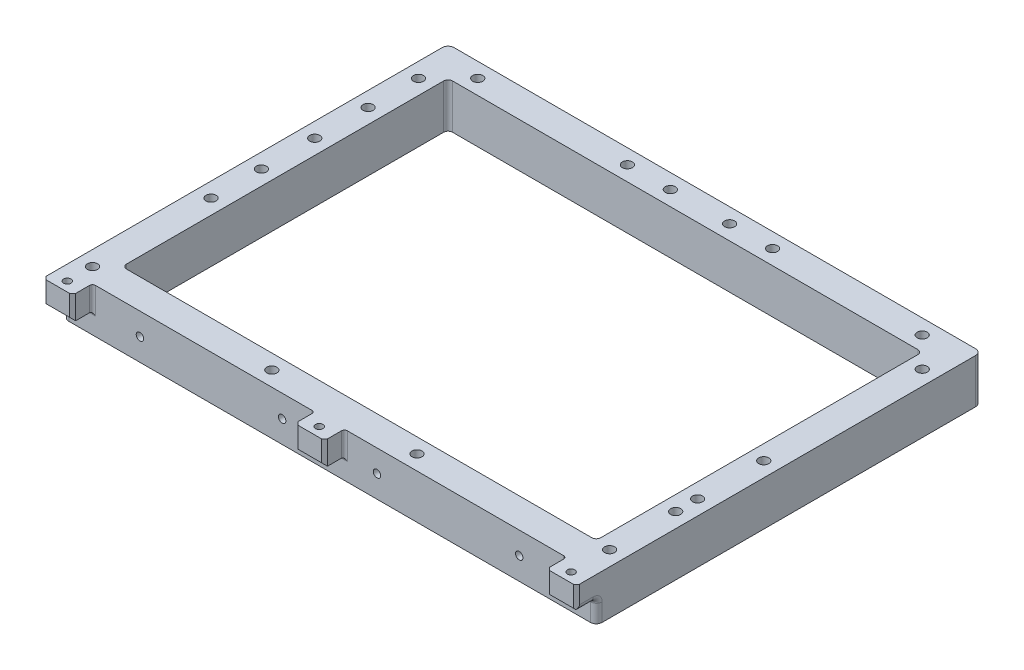
SolidWorks part; units mm, degrees
material "PLA"
ref_plane "Front Plane" through (0, 0, 0) normal (0, 0, 1) x (1, 0, 0)
ref_plane "Top Plane" through (0, 0, 0) normal (0, 1, 0) x (1, 0, 0)
ref_plane "Right Plane" through (0, 0, 0) normal (1, 0, 0) x (0, 0, -1)
sketch "Sketch1" plane through (0, 0, 0) normal (0, 1, 0) x (1, 0, 0)
  line L1 (-114.3, 82.55) -> (114.3, 82.55)
  line L2 (-114.3, 82.55) -> (-114.3, -82.55)
  line L3 (-114.3, -82.55) -> (114.3, -82.55)
  line L4 (114.3, 82.55) -> (114.3, -82.55)
  line L5 (-114.3, 82.55) -> (114.3, -82.55) construction
  line L6 (-114.3, -82.55) -> (114.3, 82.55) construction
  line L7 (-101.6, 69.85) -> (101.6, 69.85)
  line L8 (-101.6, 69.85) -> (-101.6, -69.85)
  line L9 (-101.6, -69.85) -> (101.6, -69.85)
  line L10 (101.6, 69.85) -> (101.6, -69.85)
  line L11 (-101.6, 69.85) -> (101.6, -69.85) construction
  line L12 (-101.6, -69.85) -> (101.6, 69.85) construction
  point P0 (0, 0)
  point P6 (0, 0)
  dimension "D1" = 165.1
  dimension "D2" = 139.7
  dimension "D3" = 228.6
  dimension "D4" = 203.2
extrude "Frame" add sketch "Sketch1" along normal blind 19.05
sketch "Sketch2" plane through (0, 19.05, 0) normal (0, 1, 0) x (1, 0, 0)
  line L0 (-114.3, 82.55) -> (-114.3, -82.55) construction
  line L1 (114.3, 82.55) -> (-114.3, 82.55) construction
  line L2 (0, 0) -> (0, 50000) construction
  line L3 (-101.6, 63.5) -> (-114.3, 63.5) construction
  line L4 (-101.6, 69.85) -> (-101.6, -69.85) construction
  line L5 (-95.25, 69.85) -> (-95.25, 82.55) construction
  line L6 (101.6, 69.85) -> (-101.6, 69.85) construction
  circle A0 centre (-95.25, 76.2) radius 2.159
  circle A1 centre (-107.95, 63.5) radius 2.159
  circle A2 centre (95.25, 76.2) radius 2.159
  circle A3 centre (107.95, 63.5) radius 2.159
  dimension "D1" = 4.318
  dimension "D2" = 4.318
  dimension "D3" = 19.05
  dimension "D6" = 19.05
extrude "FrontWall_mountingHoles" cut sketch "Sketch2" against normal blind 7.112
sketch "Sketch3" plane through (0, 0, 82.55) normal (0, 0, 1) x (1, 0, 0)
  line L0 (0, 0) -> (0, 50000) construction
  line L1 (-114.3, 0) -> (114.3, 0) construction
  line L2 (114.3, 19.05) -> (101.6, 19.05)
  line L3 (-114.3, 19.05) -> (114.3, 19.05) construction
  line L4 (101.6, 19.05) -> (101.6, 8.89)
  line L5 (101.6, 8.89) -> (114.3, 8.89)
  line L6 (114.3, 19.05) -> (114.3, 0) construction
  line L7 (114.3, 8.89) -> (114.3, 19.05)
  line L8 (-6.35, 19.05) -> (6.35, 19.05)
  line L9 (6.35, 19.05) -> (6.35, 8.89)
  line L10 (6.35, 8.89) -> (-6.35, 8.89)
  line L11 (-6.35, 19.05) -> (-6.35, 8.89)
  line L12 (-114.3, 8.89) -> (-114.3, 19.05)
  line L13 (-101.6, 8.89) -> (-114.3, 8.89)
  line L14 (-101.6, 19.05) -> (-101.6, 8.89)
  line L15 (-114.3, 19.05) -> (-101.6, 19.05)
  point P4 (0, 0)
  point P19 (0, 8.89)
  point P20 (0, 19.05)
  dimension "D1" = 10.16
  dimension "D2" = 12.7
  dimension "D3" = 10.16
  dimension "D4" = 12.7
extrude "Boss-Extrude2" add sketch "Sketch3" along normal blind 8.89
sketch "Sketch4" plane through (0, 19.05, 0) normal (0, 1, 0) x (1, 0, 0)
  line L0 (-114.3, -82.55) -> (114.3, -82.55) construction
  line L1 (-107.95, -91.44) -> (-107.95, -82.55) construction
  line L2 (-107.95, -82.55) -> (-107.95, -86.995) construction
  line L3 (-107.95, -86.995) -> (-101.6, -86.995) construction
  line L4 (0, -82.55) -> (0, -91.44) construction
  line L12 (114.3, -91.44) -> (114.3, 82.55)
  line L13 (114.3, 82.55) -> (-114.3, 82.55)
  line L14 (-114.3, 82.55) -> (-114.3, -91.44)
  line L15 (-114.3, -91.44) -> (-101.6, -91.44)
  line L16 (-101.6, -91.44) -> (-101.6, -82.55)
  line L17 (-101.6, -82.55) -> (-6.35, -82.55)
  line L18 (-6.35, -82.55) -> (-6.35, -91.44)
  line L19 (-6.35, -91.44) -> (6.35, -91.44)
  line L20 (6.35, -91.44) -> (6.35, -82.55)
  line L21 (6.35, -82.55) -> (101.6, -82.55)
  line L22 (101.6, -82.55) -> (101.6, -91.44)
  line L23 (101.6, -91.44) -> (114.3, -91.44)
  line L24 (114.3, -91.44) -> (114.3, 82.55) construction
  line L25 (114.3, 82.55) -> (-114.3, 82.55) construction
  line L26 (-114.3, 82.55) -> (-114.3, -91.44) construction
  line L27 (-114.3, -91.44) -> (-101.6, -91.44) construction
  line L28 (-101.6, -91.44) -> (-101.6, -82.55) construction
  line L29 (-101.6, -82.55) -> (-6.35, -82.55) construction
  line L30 (-6.35, -82.55) -> (-6.35, -91.44) construction
  line L31 (-6.35, -91.44) -> (6.35, -91.44) construction
  line L32 (6.35, -91.44) -> (6.35, -82.55) construction
  line L33 (6.35, -82.55) -> (101.6, -82.55) construction
  line L34 (101.6, -82.55) -> (101.6, -91.44) construction
  line L35 (101.6, -91.44) -> (114.3, -91.44) construction
  circle A0 centre (-107.95, -86.995) radius 1.5875
  circle A1 centre (0, -86.995) radius 1.5875
  circle A2 centre (107.95, -86.995) radius 1.5875
  dimension "D2" = 3.175
  dimension "D3" = 3.175
  dimension "D1" = 0
extrude "Cut-Extrude2" cut sketch "Sketch4" against normal through all
sketch "Sketch5" plane through (0, 0, 82.55) normal (0, 0, 1) x (1, 0, 0)
  line L0 (0, 0) -> (0, 19.05) construction
  line L1 (-114.3, 0) -> (114.3, 0) construction
  line L2 (6.35, 19.05) -> (-6.35, 19.05) construction
  circle A0 centre (-20.32, 9.525) radius 1.5875
  circle A1 centre (-81.28, 9.525) radius 1.5875
  circle A2 centre (81.28, 9.525) radius 1.5875
  circle A3 centre (20.32, 9.525) radius 1.5875
  dimension "D1" = 3.175
  dimension "D2" = 3.175
  dimension "D3" = 20.32
  dimension "D4" = 81.28
  dimension "D5" = 9.525
  dimension "D6" = 9.525
extrude "Cut-Extrude3" cut sketch "Sketch5" against normal up to surface (12.7 mm away) up to face at (0, 9.525, 69.85)
fillet "Fillet3" radius 1.905 4 edges at (101.6, 9.525, 69.85) (-101.6, 9.525, 69.85) (-101.6, 9.525, -69.85) (101.6, 9.525, -69.85)
sketch "Sketch6" plane through (0, 19.05, 0) normal (0, 1, 0) x (1, 0, 0)
  line L0 (114.3, -91.44) -> (114.3, 82.55) construction
  line L2 (99.695, 69.85) -> (-99.695, 69.85) construction
  circle A0 centre (107.95, -4.445) radius 2.159
  circle A1 centre (107.95, -32.766) radius 2.159
  circle A2 centre (107.95, -42.164) radius 2.159
  circle A3 centre (107.95, -70.485) radius 2.159
  dimension "D1" = 4.318
  dimension "D2" = 4.318
  dimension "D3" = 4.318
  dimension "D4" = 4.318
  dimension "D5" = 6.35
  dimension "D6" = 6.35
  dimension "D7" = 6.35
  dimension "D8" = 6.35
  dimension "D11" = 112.014
  dimension "D12" = 140.335
  dimension "D9" = 74.295
  dimension "D10" = 102.616
extrude "Linkage_RHS_MountingHoles" cut sketch "Sketch6" against normal blind 7.112
sketch "Sketch7" plane through (0, 19.05, 0) normal (0, 1, 0) x (1, 0, 0)
  line L0 (-114.3, 82.55) -> (-114.3, -91.44) construction
  line L1 (99.695, 69.85) -> (-99.695, 69.85) construction
  circle A0 centre (-107.95, 41.91) radius 2.159
  circle A1 centre (-107.95, 19.05) radius 2.159
  circle A2 centre (-107.95, -3.81) radius 2.159
  dimension "D1" = 4.318
  dimension "D2" = 4.318
  dimension "D3" = 4.318
  dimension "D5" = 6.35
  dimension "D4" = 6.35
  dimension "D6" = 27.94
  dimension "D7" = 50.8
  dimension "D8" = 73.66
  dimension "D9" = 6.35
extrude "Linkage-LHS-MountingHoles" cut sketch "Sketch7" against normal blind 7.112
sketch "Sketch11" plane through (0, 0, 91.44) normal (0, 0, 1) x (1, 0, 0)
  line L4 (-114.3, 8.89) -> (-101.6, 8.89)
  line L5 (-101.6, 8.89) -> (-101.6, 19.05)
  line L6 (-101.6, 19.05) -> (-114.3, 19.05)
  line L7 (-114.3, 19.05) -> (-114.3, 8.89)
  line L8 (-114.3, 8.89) -> (-101.6, 8.89)
  line L9 (-101.6, 8.89) -> (-101.6, 19.05)
  line L10 (-101.6, 19.05) -> (-114.3, 19.05)
  line L11 (-114.3, 19.05) -> (-114.3, 8.89)
  line L12 (6.35, 8.89) -> (6.35, 19.05)
  line L13 (6.35, 19.05) -> (-6.35, 19.05)
  line L14 (-6.35, 19.05) -> (-6.35, 8.89)
  line L15 (-6.35, 8.89) -> (6.35, 8.89)
  line L16 (6.35, 8.89) -> (6.35, 19.05)
  line L17 (6.35, 19.05) -> (-6.35, 19.05)
  line L18 (-6.35, 19.05) -> (-6.35, 8.89)
  line L19 (-6.35, 8.89) -> (6.35, 8.89)
  line L20 (114.3, 8.89) -> (114.3, 19.05)
  line L21 (114.3, 19.05) -> (101.6, 19.05)
  line L22 (101.6, 19.05) -> (101.6, 8.89)
  line L23 (101.6, 8.89) -> (114.3, 8.89)
  line L24 (114.3, 8.89) -> (114.3, 19.05)
  line L25 (114.3, 19.05) -> (101.6, 19.05)
  line L26 (101.6, 19.05) -> (101.6, 8.89)
  line L27 (101.6, 8.89) -> (114.3, 8.89)
  dimension "D1" = 0
  dimension "D2" = 0
  dimension "D3" = 0
extrude "Cut-Extrude6" cut sketch "Sketch11" against normal blind 0.381
fillet "Fillet2" radius 1.27 7 edges at (107.95, 8.89, 82.55) (0, 8.89, 82.55) (-107.95, 8.89, 82.55) (101.6, 13.97, 82.55) (6.35, 13.97, 82.55) (-6.35, 13.97, 82.55) (-101.6, 13.97, 82.55)
chamfer "Chamfer1" distance 1.27 angle 45 9 edges at (101.6, 13.97, 91.059) (6.35, 13.97, 91.059) (-6.35, 13.97, 91.059) (-101.6, 13.97, 91.059) (107.95, 8.89, 91.059) (0, 8.89, 91.059) (-107.95, 8.89, 91.059) (114.3, 13.97, 91.059) (-114.3, 13.97, 91.059)
sketch "Sketch12" plane through (0, 19.05, 0) normal (0, 1, 0) x (1, 0, 0)
  line L0 (0, 82.55) -> (0, 0) construction
  line L1 (114.3, 82.55) -> (-114.3, 82.55) construction
  line L2 (0, 0) -> (-101.6, 0) construction
  line L3 (-101.6, 67.945) -> (-101.6, -67.945) construction
  line L4 (99.695, 69.85) -> (-99.695, 69.85) construction
  circle A0 centre (-31.115, 76.2) radius 2.159
  circle A1 centre (31.115, 76.2) radius 2.159
  circle A2 centre (31.115, -76.2) radius 2.159
  circle A3 centre (-31.115, -76.2) radius 2.159
  dimension "D1" = 4.318
  dimension "D3" = 62.23
  dimension "D2" = 6.35
extrude "Caster_Wheel_Mount" cut sketch "Sketch12" against normal blind 7.112
sketch "Sketch13" plane through (0, 19.05, 0) normal (0, 1, 0) x (1, 0, 0)
  line L0 (0, 0) -> (0, 82.55) construction
  line L1 (114.3, 82.55) -> (-114.3, 82.55) construction
  line L2 (-5.6278, 82.55) -> (-5.6278, 69.85) construction
  line L3 (99.695, 69.85) -> (-99.695, 69.85) construction
  line L4 (-5.6278, 76.2) -> (-12.7, 76.2) construction
  circle A0 centre (-12.7, 76.2) radius 2.159
  circle A1 centre (12.7, 76.2) radius 2.159
  dimension "D1" = 4.318
  dimension "D2" = 25.4
extrude "FrontBrace_Mount" cut sketch "Sketch13" against normal blind 7.112
sketch "Sketch14" plane through (0, 19.05, 0) normal (0, 1, 0) x (1, 0, 0)
  line L0 (-114.3, -50.8) -> (-101.6, -50.8) construction
  line L1 (-114.3, 82.55) -> (-114.3, -89.789) construction
  line L2 (-101.6, 67.945) -> (-101.6, -67.945) construction
  line L3 (-107.95, -76.2) -> (-107.95, -25.4) construction
  line L4 (99.695, 69.85) -> (-99.695, 69.85) construction
  circle A0 centre (-107.95, -25.4) radius 2.159
  circle A1 centre (-107.95, -76.2) radius 2.159
  point P10 (-107.95, -50.8)
  dimension "D1" = 4.318
  dimension "D2" = 50.8
  dimension "D3" = 120.65
extrude "USB_HUB_Switch_Mount_Holes" cut sketch "Sketch14" against normal blind 7.112
fillet "Fillet4" radius 2.54 8 edges at (114.3, 8.89, 86.8045) (114.3, 8.518, 82.922) (-114.3, 8.89, 86.8045) (-114.3, 8.518, 82.922) (114.3, 3.81, 82.55) (-114.3, 3.81, 82.55) (114.3, 9.525, -82.55) (-114.3, 9.525, -82.55)
equation "\"D3@Sketch3\"=\"D1@Sketch3\""
equation "\"D2@Sketch6\"=\"D1@Sketch6\""
equation "\"D3@Sketch6\"=\"D1@Sketch6\""
equation "\"D4@Sketch6\"=\"D1@Sketch6\""
equation "\"D6@Sketch6\"=\"D5@Sketch6\""
equation "\"D8@Sketch6\"=\"D7@Sketch6\""
equation "\"D2@Sketch7\"=\"D1@Sketch7\""
equation "\"D3@Sketch7\"=\"D1@Sketch7\""
equation "\"D2@Sketch2\"=\"D1@Sketch2\""
